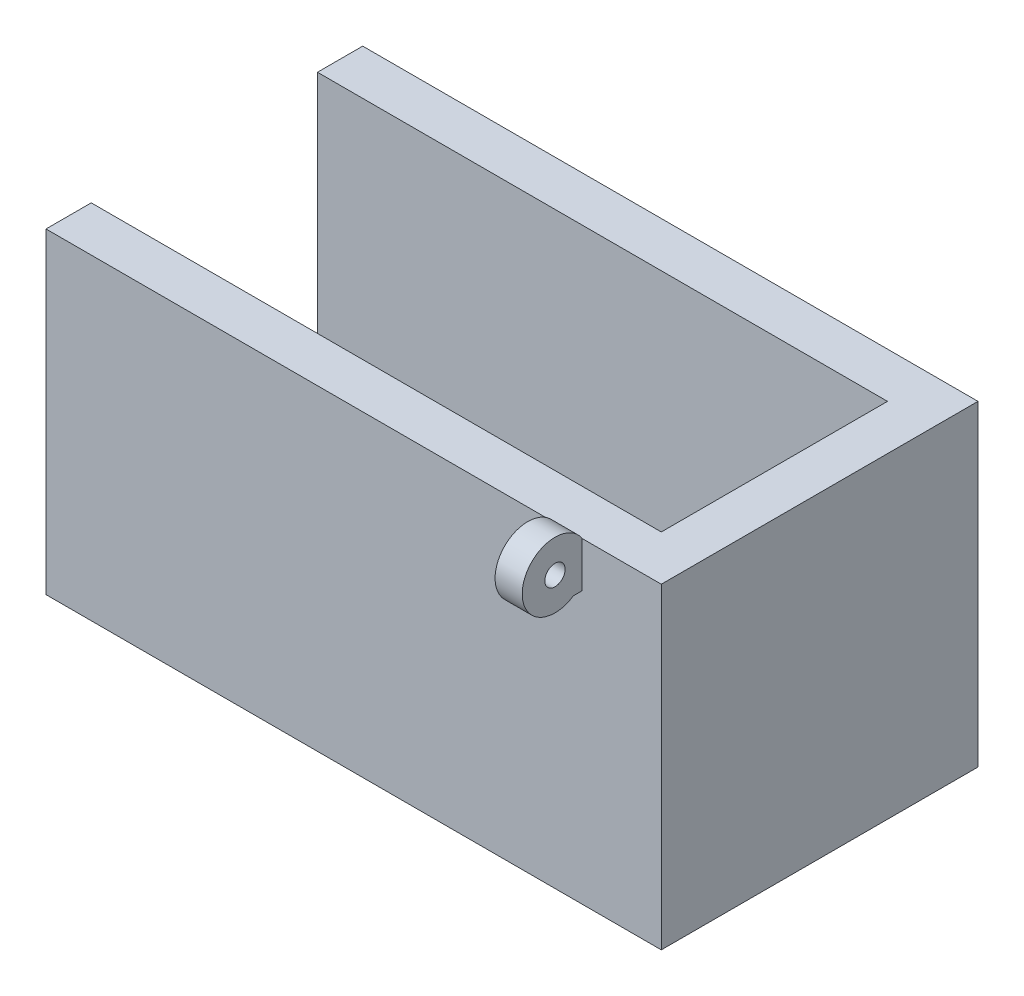
SolidWorks part; units mm, degrees
ref_plane "前基準面" through (0, 0, 0) normal (0, 0, 1) x (1, 0, 0)
ref_plane "上基準面" through (0, 0, 0) normal (0, 1, 0) x (1, 0, 0)
ref_plane "右基準面" through (0, 0, 0) normal (1, 0, 0) x (0, 0, -1)
sketch "草圖1" plane through (0, 0, 0) normal (0, 1, 0) x (1, 0, 0)
  line L1 (-109.4634, 62.6098) -> (162.5366, 62.6098)
  line L2 (-109.4634, 62.6098) -> (-109.4634, -77.3902)
  line L3 (-109.4634, -77.3902) -> (162.5366, -77.3902)
  line L4 (162.5366, 62.6098) -> (162.5366, -77.3902)
  dimension "D1" = 272
  dimension "D2" = 140
extrude "填料-伸長1" add sketch "草圖1" along normal blind 140
sketch "草圖2" plane through (0, 140, 0) normal (0, 1, 0) x (1, 0, 0)
  line L0 (-109.4634, 62.6098) -> (-109.4634, -77.3902) construction
  line L1 (-109.4634, 42.6098) -> (142.5366, 42.6098)
  line L2 (-109.4634, 42.6098) -> (-109.4634, -57.3902)
  line L3 (-109.4634, -57.3902) -> (142.5366, -57.3902)
  line L4 (142.5366, 42.6098) -> (142.5366, -57.3902)
  line L5 (162.5366, 62.6098) -> (-109.4634, 62.6098) construction
  line L6 (-109.4634, -77.3902) -> (162.5366, -77.3902) construction
  line L7 (162.5366, -77.3902) -> (162.5366, 62.6098) construction
  dimension "D1" = 20
  dimension "D2" = 20
  dimension "D3" = 20
extrude "除料-伸長1" cut sketch "草圖2" against normal blind 110
sketch "草圖3" plane through (-109.4634, 0, 0) normal (-1, 0, 0) x (0, 0, 1)
  line L0 (57.3902, 30) -> (-42.6098, 30) construction
  line L1 (-42.6098, 20) -> (57.3902, 20)
  line L2 (-42.6098, 20) -> (-42.6098, 7)
  line L3 (-42.6098, 7) -> (57.3902, 7)
  line L4 (57.3902, 20) -> (57.3902, 7)
  line L5 (-62.6098, 0) -> (77.3902, 0) construction
  line L6 (-62.6098, 140) -> (-62.6098, 0) construction
  dimension "D1" = 10
  dimension "D2" = 7
  dimension "D3" = 100
  dimension "D4" = 20
extrude "除料-伸長2" cut sketch "草圖3" against normal blind 100
sketch "草圖5" plane through (0, 30, 0) normal (0, 1, 0) x (1, 0, 0)
  line L0 (-109.4634, -7.3902) -> (-89.4634, -7.3902) construction
  line L1 (-109.4634, 42.6098) -> (-109.4634, -57.3902) construction
  point P4 (0, 0)
  dimension "D1" = 20
sketch "草圖7" plane through (0, 30, 0) normal (0, 1, 0) x (1, 0, 0)
  circle A0 centre (-89.4634, -7.3902) radius 3
  dimension "D1" = 6
extrude "除料-伸長3" cut sketch "草圖7" against normal through all
sketch "草圖8" plane through (0, 0, 77.3902) normal (0, 0, 1) x (1, 0, 0)
  line L0 (162.5366, 140) -> (162.5366, 0) construction
  line L1 (115.5366, 132) -> (127.5366, 132)
  line L2 (115.5366, 132) -> (115.5366, 120)
  line L3 (115.5366, 120) -> (127.5366, 120)
  line L4 (127.5366, 132) -> (127.5366, 120)
  line L5 (-109.4634, 140) -> (162.5366, 140) construction
  dimension "D1" = 35
  dimension "D2" = 8
  dimension "D3" = 12
  dimension "D4" = 12
extrude "填料-伸長2" add sketch "草圖8" along normal blind 10
sketch "草圖9" plane through (127.5366, 0, 0) normal (1, 0, 0) x (0, 0, -1)
  line L0 (-87.3902, 132) -> (-89.3902, 132) construction
  circle A0 centre (-89.3902, 132) radius 4.49
  dimension "D1" = 8.98
extrude "伸長-薄件1" add sketch "草圖9" against normal blind 12 thin
sketch "草圖11" plane through (127.5366, 0, 0) normal (1, 0, 0) x (0, 0, -1)
  line L0 (-1093.8802, 132) -> (48906.1198, 132) construction
  line L1 (-89.3902, -872.49) -> (-89.3902, 49127.51) construction
  circle A2 centre (-89.3902, 132) radius 4.49
  dimension "D1" = 8.98
extrude "除料-伸長5" cut sketch "草圖11" against normal through all
